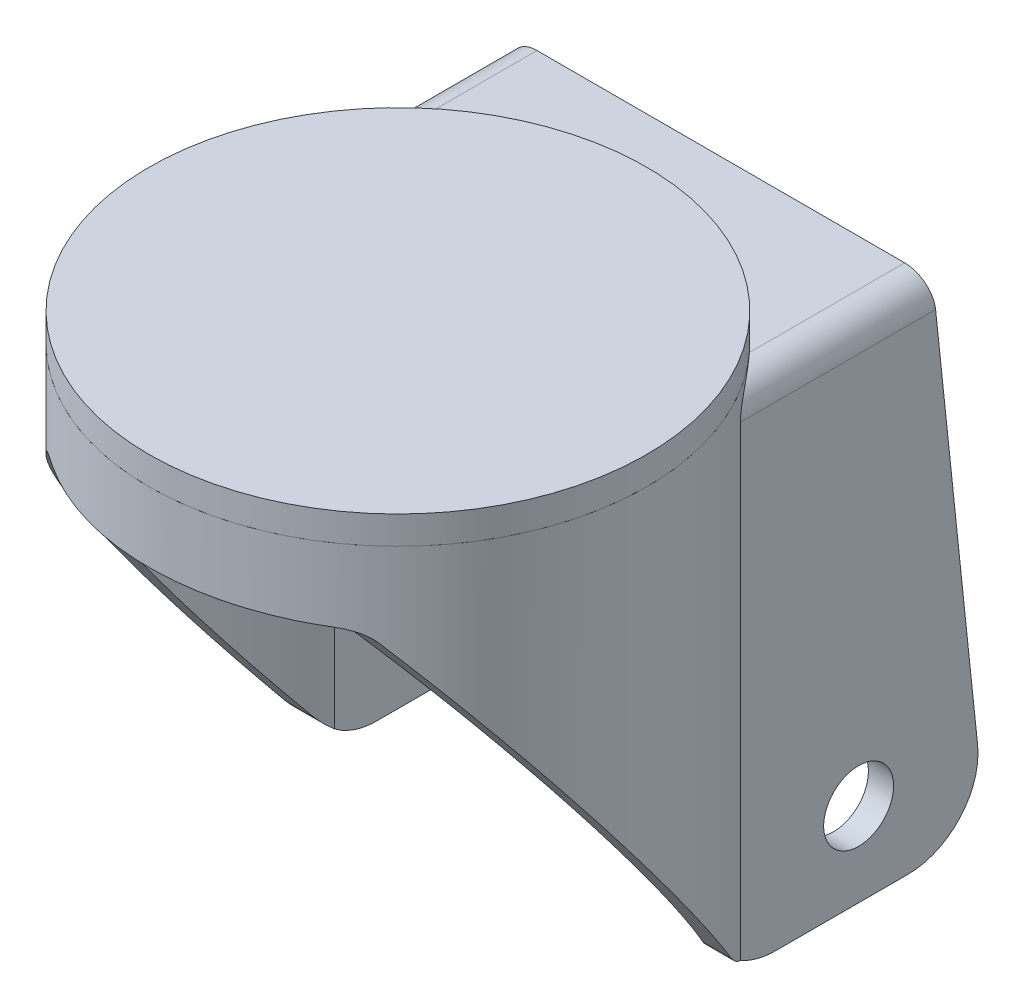
SolidWorks part; units mm, degrees
ref_plane "Front Plane" through (0, 0, 0) normal (0, 0, 1) x (1, 0, 0)
ref_plane "Top Plane" through (0, 0, 0) normal (0, 1, 0) x (1, 0, 0)
ref_plane "Right Plane" through (0, 0, 0) normal (1, 0, 0) x (0, 0, -1)
sketch "Sketch1" plane through (0, 0, 0) normal (0, 1, 0) x (1, 0, 0)
  circle A0 centre (0, 0) radius 17.8
  dimension "D1" = 35.6
extrude "Boss-Extrude1" add sketch "Sketch1" against normal blind 2
sketch "Sketch2" plane through (0, -2, 0) normal (0, -1, 0) x (1, 0, 0)
  line L1 (-15.15, 23.1) -> (15.15, 23.1)
  line L2 (-15.15, 23.1) -> (-15.15, -23.1)
  line L3 (-15.15, -23.1) -> (15.15, -23.1)
  line L4 (15.15, 23.1) -> (15.15, -23.1)
  line L5 (-15.15, 23.1) -> (15.15, -23.1) construction
  line L6 (-15.15, -23.1) -> (15.15, 23.1) construction
  circle A1 centre (0, 0) radius 17.8
  circle A2 centre (0, 0) radius 17.8
  point P7 (0, -17.8)
  point P8 (0, -23.1)
  circle M3 centre (0, 0) radius 17.8
  dimension "D2" = 30.3
  dimension "D3" = 5.3
  dimension "D1" = 0
extrude "Boss-Extrude2" add sketch "Sketch2" along normal blind 36 separate body contours L4 M3 | L4 L2 M3 | L4 L2 L3 M3 | L2 M3
sketch "Sketch3" plane through (0, -38, 0) normal (0, -1, 0) x (1, 0, 0)
  line L0 (-13.35, -8.8192) -> (-13.35, -21.3)
  line L1 (-13.35, -21.3) -> (13.35, -21.3)
  line L2 (13.35, -21.3) -> (13.35, -8.8192)
  line L3 (-15.15, -9.3444) -> (-15.15, -23.1)
  line L4 (-15.15, -23.1) -> (15.15, -23.1)
  line L5 (15.15, -23.1) -> (15.15, -9.3444)
  line L6 (-15.15, -9.3444) -> (-15.15, -23.1)
  line L7 (-15.15, -23.1) -> (15.15, -23.1)
  line L8 (15.15, -23.1) -> (15.15, -9.3444)
  line L10 (13.35, -21.3) -> (-13.35, -21.3)
  line L11 (13.35, -21.3) -> (13.35, -23.1)
  line L12 (13.35, -23.1) -> (-13.35, -23.1)
  line L13 (-13.35, -21.3) -> (-13.35, -23.1)
  arc A0 (13.35, -8.8192) -> (-13.35, -8.8192) centre (0, 0) ccw
  arc A1 (15.15, -9.3444) -> (-15.15, -9.3444) centre (0, 0) ccw
  arc A2 (15.15, -9.3444) -> (-15.15, -9.3444) centre (0, 0) ccw
  dimension "D1" = 0
  dimension "D2" = 1.8
extrude "Cut-Extrude1" cut sketch "Sketch3" against normal offset from surface (34.2 mm away) 1.8 contours L2 A0 L0 L1 | L1 L13 L7 L11 up to face at (0, -2, -9.4361)
ref_plane "Plane1" through (17.8, 0, 0) normal (1, 0, 0) x (0, 0, -1)
sketch "Sketch4" plane through (17.8, 0, 0) normal (1, 0, 0) x (0, 0, -1)
  line L0 (9.3444, -38) -> (-13.8094, -7.2739)
  line L1 (-17.8, -2) -> (-17.8, -7)
  line L2 (-17.8, -2) -> (-17.8, -38) construction
  line L3 (-13.8094, -7.2739) -> (-17.8, -7)
  line L4 (9.3444, -38) -> (9.3444, -2) construction
  line L5 (-17.8, -7) -> (-17.8, -38)
  line L6 (-17.8, -38) -> (9.3444, -38) construction
  line L7 (-17.8, -38) -> (9.3444, -38)
  point P3 (-17.8, -2)
  dimension "D1" = 5
  dimension "D2" = 4
  dimension "D3" = 37
extrude "Cut-Extrude2" cut sketch "Sketch4" against normal through all contours L5 L7 L0 L3
sketch "Sketch5" plane through (15.15, 0, 0) normal (1, 0, 0) x (0, 0, -1)
  line L0 (23.1, -2) -> (26.9, -38)
  line L1 (23.1, -38) -> (26.9, -38)
  line L2 (23.1, -2) -> (23.1, -38)
  dimension "D1" = 36.2
extrude "Boss-Extrude3" add sketch "Sketch5" against normal up to surface (30.3 mm away) up to face at (-15.15, -20, -16.2222)
sketch "Sketch6" plane through (0, -38, 0) normal (0, -1, 0) x (1, 0, 0)
  line L0 (-15.15, -26.9) -> (15.15, -26.9) construction
  line L1 (13.35, -23.1) -> (-13.35, -23.1)
  line L2 (13.35, -23.1) -> (13.35, -26.9)
  line L3 (13.35, -26.9) -> (-13.35, -26.9)
  line L4 (-13.35, -23.1) -> (-13.35, -26.9)
  line L5 (-13.35, -9.3444) -> (-13.35, -23.1) construction
extrude "Cut-Extrude3" cut sketch "Sketch6" against normal offset from surface (34.2 mm away) 1.8 up to face at (0, -2, -9.4361)
sketch "Sketch7" plane through (15.15, 0, 0) normal (1, 0, 0) x (0, 0, -1)
  line L0 (9.3444, -38) -> (9.3444, -2) construction
  line L1 (26.9, -38) -> (23.1, -2) construction
  line L2 (9.3444, -32) -> (26.2667, -32) construction
  line L3 (9.3444, -38) -> (26.9, -38) construction
  circle A0 centre (17.8055, -32) radius 2.5
  dimension "D1" = 5
  dimension "D2" = 6
  dimension "D3" = 16.9223
  dimension "D4" = 8.4611
extrude "Cut-Extrude4" cut sketch "Sketch7" against normal up to surface (30.3 mm away) up to face at (-15.15, -20, -17.1722)
fillet "Fillet1" radius 2 4 edges at (-9.6561, -7.2739, 13.8094) (9.6561, -7.2739, 13.8094) (-15.15, -2, -16.2222) (15.15, -2, -16.2222)
fillet "Fillet2" radius 5 2 edges at (-14.25, -38, -26.9) (14.25, -38, -26.9)
fillet "Fillet3" radius 5 1 edges at (-14.25, -38, -9.3444)
equation "\"D4@Sketch7\"=\"D3@Sketch7\"/2"
